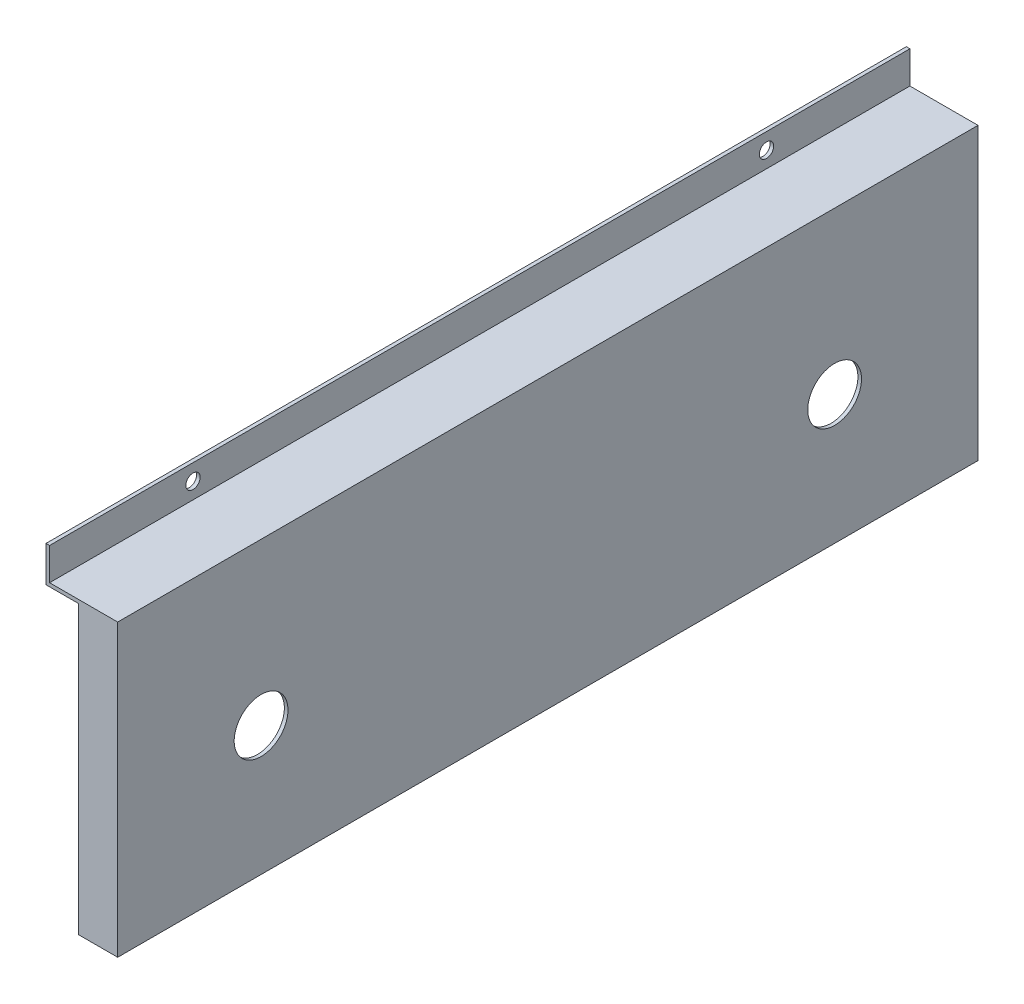
SolidWorks part; units mm, degrees
ref_plane "Alzado" through (0, 0, 0) normal (0, 0, 1) x (1, 0, 0)
ref_plane "Planta" through (0, 0, 0) normal (0, 1, 0) x (1, 0, 0)
ref_plane "Vista lateral" through (0, 0, 0) normal (1, 0, 0) x (0, 0, -1)
sketch "Croquis1" plane through (0, 0, 0) normal (0, 0, 1) x (1, 0, 0)
  line L1 (-2.6694, 23.8026) -> (17.3306, 23.8026)
  line L2 (-2.6694, 23.8026) -> (-2.6694, -76.1974)
  line L3 (-2.6694, -76.1974) -> (17.3306, -76.1974)
  line L4 (17.3306, 23.8026) -> (17.3306, -76.1974)
  dimension "D1" = 20
extrude "Saliente-Extruir1" add sketch "Croquis1" along normal blind 240
sketch "Croquis2" plane through (0, 0, 240) normal (0, 0, 1) x (1, 0, 0)
  line L1 (-2.6694, 23.8026) -> (-2.6694, -76.1974) construction
  line L2 (17.3306, 23.8026) -> (-1.6694, 23.8026)
  line L3 (17.3306, 23.8026) -> (17.3306, 14.8026)
  line L4 (17.3306, 14.8026) -> (-1.6694, 14.8026)
  line L5 (-1.6694, 23.8026) -> (-1.6694, 14.8026)
  dimension "D1" = 1
  dimension "D2" = 9
extrude "Cortar-Extruir1" cut sketch "Croquis2" against normal up to surface (240 mm away) up to face at (7.3306, -26.1974, 0)
sketch "Croquis3" plane through (-2.6694, 0, 0) normal (-1, 0, 0) x (0, 0, 1)
  line L0 (240, -76.1974) -> (0, -76.1974) construction
  line L1 (1, -76.1974) -> (239, -76.1974)
  line L2 (1, -76.1974) -> (1, 13.8026)
  line L3 (1, 13.8026) -> (239, 13.8026)
  line L4 (239, -76.1974) -> (239, 13.8026)
  line L5 (0, 23.8026) -> (0, -76.1974) construction
  line L6 (240, 23.8026) -> (240, -76.1974) construction
  line L7 (240, 23.8026) -> (0, 23.8026) construction
  circle A0 centre (40, 19.3026) radius 2
  circle A1 centre (200, 19.3026) radius 2
  dimension "D4" = 40
  dimension "D1" = 1
  dimension "D2" = 1
  dimension "D3" = 90
  dimension "D5" = 4.5
  dimension "D6" = 4.5
  dimension "D7" = 40
extrude "Cortar-Extruir2" cut sketch "Croquis3" against normal blind 19
sketch "Croquis4" plane through (-2.6694, 0, 0) normal (-1, 0, 0) x (0, 0, 1)
  line L1 (1, 13.8026) -> (0, 13.8026)
  line L2 (1, 13.8026) -> (1, -76.1974)
  line L3 (1, -76.1974) -> (0, -76.1974)
  line L4 (0, 13.8026) -> (0, -76.1974)
  line L5 (239, 13.8026) -> (240, 13.8026)
  line L6 (239, 13.8026) -> (239, -76.1974)
  line L7 (239, -76.1974) -> (240, -76.1974)
  line L8 (240, 13.8026) -> (240, -76.1974)
extrude "Cortar-Extruir3" cut sketch "Croquis4" against normal blind 9
sketch "Croquis5" plane through (17.3306, 0, 0) normal (1, 0, 0) x (0, 0, -1)
  line L1 (0, -76.1974) -> (0, 14.8026) construction
  line L2 (-240, -76.1974) -> (-240, 14.8026) construction
  line L3 (0, -76.1974) -> (0, 14.8026) construction
  line L4 (-240, -76.1974) -> (0, -76.1974)
  line L5 (-240, -76.1974) -> (-240, -66.1974)
  line L6 (-240, -66.1974) -> (0, -66.1974)
  line L7 (0, -76.1974) -> (0, -66.1974)
  circle A0 centre (-200, -30.1974) radius 7.5
  circle A1 centre (-40, -30.1974) radius 7.5
  point P6 (0, -30.6974)
  point P9 (-240, -30.6974)
  dimension "D3" = 40
  dimension "D4" = 40
extrude "Cortar-Extruir5" cut sketch "Croquis5" against normal blind 20
